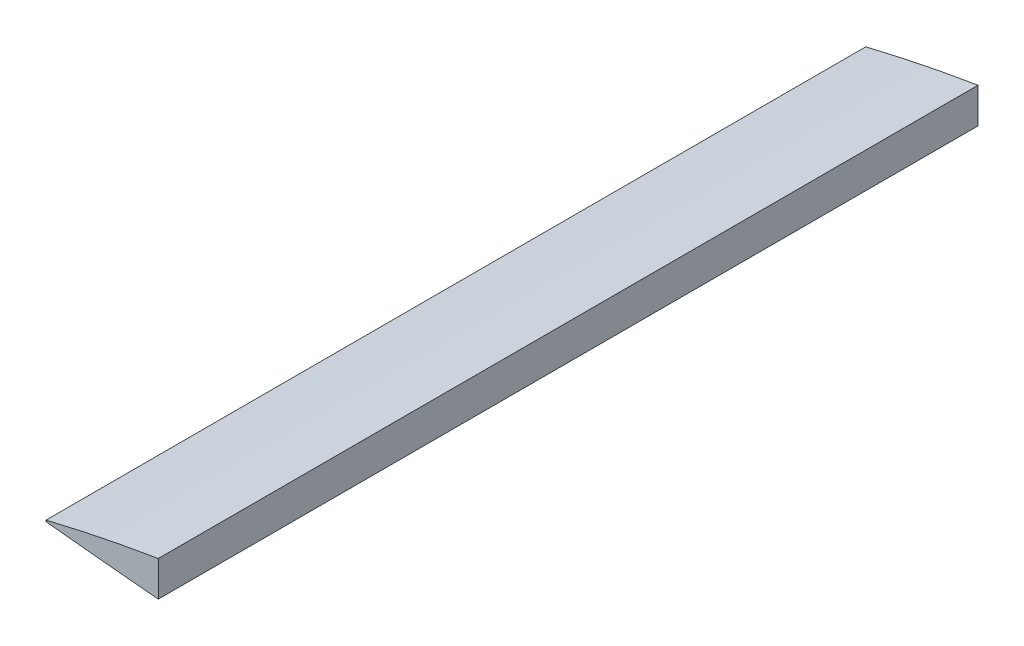
SolidWorks part; units mm, degrees
ref_plane "Front Plane" through (0, 0, 0) normal (0, 0, 1) x (1, 0, 0)
ref_plane "Top Plane" through (0, 0, 0) normal (0, 1, 0) x (1, 0, 0)
ref_plane "Right Plane" through (0, 0, 0) normal (1, 0, 0) x (0, 0, -1)
sketch "Sketch1" plane through (0, 0, 0) normal (0, 0, 1) x (1, 0, 0)
  line L0 (-238.5264, 17.5878) -> (-238.5264, -8.7167)
  line L1 (-322.333, 0.5148) -> (-322.333, -0.5066)
  spline S0 degree 3 poles (-238.5264, 17.5878) (-240.9741, 17.1819) (-246.9298, 16.1941) (-256.1812, 14.5461) (-266.0707, 12.7093) (-275.3065, 10.9116) (-283.8343, 9.1839) (-291.6033, 7.5511) (-298.5679, 6.0388) (-304.6872, 4.6711) (-309.9259, 3.4706) (-314.2535, 2.4578) (-317.6452, 1.6505) (-320.0818, 1.0631) (-321.538, 0.709) (-322.1805, 0.552) (-322.333, 0.5148) knots 0 0 0 0 0.087007 0.211705 0.329527 0.439741 0.541661 0.634652 0.718135 0.791585 0.85454 0.906603 0.947445 0.976805 0.994497 1 1 1 1
  spline S1 degree 3 poles (-238.5264, -8.7167) (-240.6457, -8.5246) (-246.2789, -8.0139) (-255.2335, -7.1819) (-265.179, -6.245) (-274.4894, -5.3529) (-283.1057, -4.5145) (-290.9725, -3.7372) (-298.0392, -3.0286) (-304.2602, -2.3953) (-309.5949, -1.8468) (-314.0082, -1.3828) (-317.4721, -1.0277) (-319.9612, -0.741) (-321.4641, -0.6201) (-322.142, -0.5059) (-322.3217, -0.5065) (-322.333, -0.5066) knots 0 0 0 0 0.075811 0.201508 0.320388 0.431695 0.534719 0.628797 0.713321 0.78774 0.851567 0.90438 0.945827 0.975633 0.993597 0.999599 1 1 1 1
extrude "Boss-Extrude1" add sketch "Sketch1" against normal blind 612
ref_plane "Plane1" through (0, 0, -96.9) normal (0, 0, 1) x (1, 0, 0)
sketch "Sketch2" plane through (0, 0, -96.9) normal (0, 0, 1) x (1, 0, 0)
  line L0 (-262.25, -9.09) -> (-241.25, -9.09)
  line L1 (-241.25, -9.09) -> (-241.25, 2.41)
  line L2 (-241.25, 2.41) -> (-262.25, 2.41)
  line L3 (-262.25, 2.41) -> (-262.25, -9.09)
extrude "Cut-Extrude1" cut sketch "Sketch2" along normal blind 13
